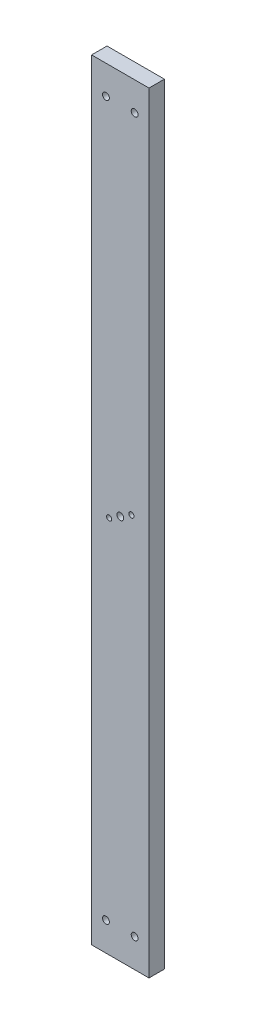
SolidWorks part; units mm, degrees
ref_plane "Front Plane" through (0, 0, 0) normal (0, 0, 1) x (1, 0, 0)
ref_plane "Top Plane" through (0, 0, 0) normal (0, 1, 0) x (1, 0, 0)
ref_plane "Right Plane" through (0, 0, 0) normal (1, 0, 0) x (0, 0, -1)
sketch "woodbase" plane through (0, 0, 0) normal (0, 0, 1) x (1, 0, 0)
  line L0 (205.6043, -11.0526) -> (440.1341, -11.0526) construction
  line L1 (291.8384, 438.9474) -> (358.8384, 438.9474)
  line L2 (291.8384, 438.9474) -> (291.8384, -461.0526)
  line L3 (291.8384, -461.0526) -> (358.8384, -461.0526)
  line L4 (358.8384, 438.9474) -> (358.8384, -461.0526)
  line L7 (325.3384, 636.1295) -> (325.3384, -740.2746) construction
  circle A0 centre (325.3384, -11.0526) radius 4
  circle A3 centre (312.3384, -19.0526) radius 3
  circle A4 centre (338.3384, -3.0526) radius 3
  circle A5 centre (308.5884, -427.5526) radius 4
  circle A6 centre (342.0884, -427.5526) radius 4
  circle A7 centre (342.0884, 405.4474) radius 4
  circle A8 centre (308.5884, 405.4474) radius 4
  dimension "D3" = 13
  dimension "D7" = 450
  dimension "D8" = 8
  dimension "D9" = 8
  dimension "D1" = 900
  dimension "D2" = 67
  dimension "D4" = 13
  dimension "D5" = 8
  dimension "D6" = 8
  dimension "D10" = 33.5
  dimension "D11" = 33.5
  dimension "D12" = 16.75
  dimension "D13" = 16.75
  dimension "D14" = 33.5
extrude "Boss-Extrude1" add sketch "woodbase" along normal blind 18
